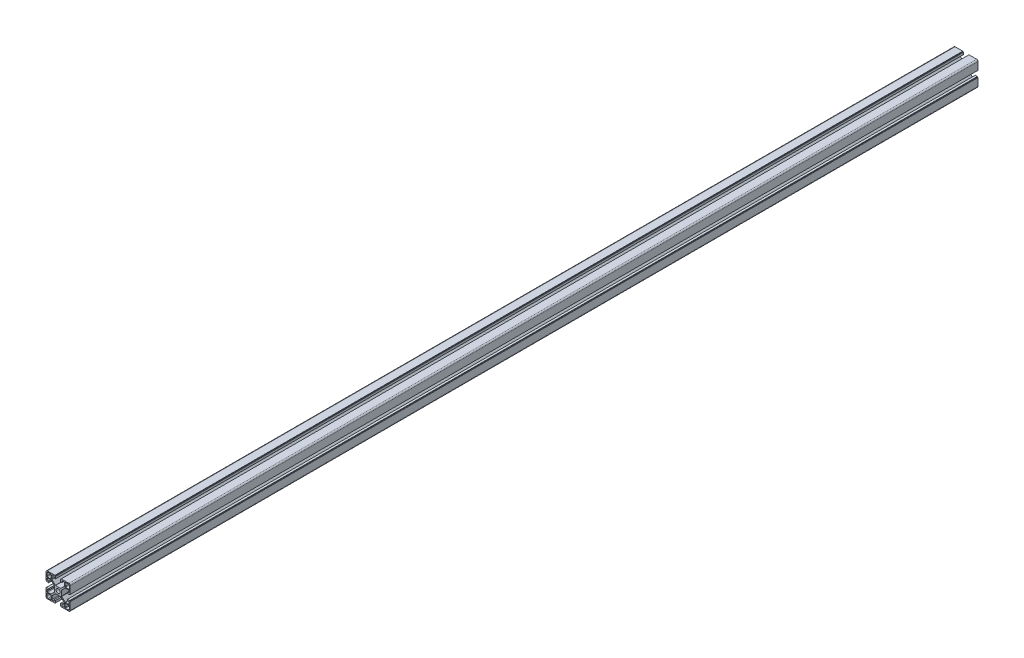
SolidWorks part; units mm, degrees
material "6063-T5"
ref_plane "Front Plane" through (0, 0, 0) normal (0, 0, 1) x (1, 0, 0)
ref_plane "Top Plane" through (0, 0, 0) normal (0, 1, 0) x (1, 0, 0)
ref_plane "Right Plane" through (0, 0, 0) normal (1, 0, 0) x (0, 0, -1)
sketch "Sketch1" plane through (0, 0, 0) normal (0, 0, 1) x (1, 0, 0)
  line L4 (20, 17.75) -> (20, 5.15)
  line L5 (0, -17.7813) -> (0, 18.2) construction
  line L6 (0, 0) -> (38.8613, 0) construction
  line L8 (18.6, 16.35) -> (18.6, 12.2)
  line L10 (11.4, 17.8) -> (11.4, 12.2)
  line L11 (-4.1, 5.85) -> (4.1, 5.85)
  line L14 (5.85, 4.1089) -> (5.85, -4.1089)
  line L17 (12.2, 11.4) -> (17.8, 11.4)
  line L24 (4.15, 19) -> (4.15, 15.4)
  line L25 (4.15, 15.4) -> (6.35, 15.4)
  line L26 (6.35, 15.4) -> (6.35, 16.95)
  line L27 (10.3, 17.2) -> (10.3, 12.0545)
  line L28 (10.0659, 11.489) -> (4.6659, 6.0845)
  line L29 (6.0841, 4.6743) -> (11.4708, 10.0655)
  line L30 (12.0367, 10.3) -> (17.2, 10.3)
  line L31 (18.2, 9.3) -> (18.2, 7.6)
  line L32 (16.95, 6.35) -> (15.4, 6.35)
  line L33 (15.4, 6.35) -> (15.4, 4.15)
  line L34 (15.4, 4.15) -> (19, 4.15)
  line L35 (18.6, 18.6) -> (18.6, -18.6) construction
  line L36 (-18.6, 18.6) -> (18.6, 18.6) construction
  line L37 (-20, 20) -> (20, 20) construction
  line L38 (20, 20) -> (20, -20) construction
  line L40 (7.6, 18.2) -> (9.3, 18.2)
  line L42 (4.15, 19) -> (5.15, 19)
  line L43 (5.15, 19) -> (5.15, 20)
  line L56 (-18.6, 18.6) -> (-18.6, -18.6) construction
  line L57 (-20, 20) -> (-20, -20) construction
  line L60 (5.15, 20) -> (17.75, 20)
  line L91 (-18.6, -18.6) -> (18.6, -18.6) construction
  line L92 (-20, -20) -> (20, -20) construction
  line L93 (12.2, 18.6) -> (16.35, 18.6)
  line L94 (17.9399, 17.9421) -> (20, 20) construction
  line L95 (0, 0) -> (11.4, 11.4094) construction
  line L101 (19, 4.15) -> (19, 5.15)
  line L102 (19, 5.15) -> (20, 5.15)
  line L104 (-5.85, 4.1089) -> (-5.85, -4.1089)
  line L105 (-19, 5.15) -> (-20, 5.15)
  line L106 (-19, 4.15) -> (-19, 5.15)
  line L107 (-12.2, 18.6) -> (-16.35, 18.6)
  line L108 (-5.15, 20) -> (-17.75, 20)
  line L109 (-5.15, 19) -> (-5.15, 20)
  line L110 (-4.15, 19) -> (-5.15, 19)
  line L111 (-7.6, 18.2) -> (-9.3, 18.2)
  line L112 (-15.4, 4.15) -> (-19, 4.15)
  line L113 (-15.4, 6.35) -> (-15.4, 4.15)
  line L114 (-16.95, 6.35) -> (-15.4, 6.35)
  line L115 (-18.2, 9.3) -> (-18.2, 7.6)
  line L116 (-12.0367, 10.3) -> (-17.2, 10.3)
  line L117 (-6.0841, 4.6743) -> (-11.4708, 10.0655)
  line L118 (-10.0659, 11.489) -> (-4.6659, 6.0845)
  line L119 (-10.3, 17.2) -> (-10.3, 12.0545)
  line L120 (-6.35, 15.4) -> (-6.35, 16.95)
  line L121 (-4.15, 15.4) -> (-6.35, 15.4)
  line L122 (-4.15, 19) -> (-4.15, 15.4)
  line L123 (-12.2, 11.4) -> (-17.8, 11.4)
  line L124 (-11.4, 17.8) -> (-11.4, 12.2)
  line L125 (-18.6, 16.35) -> (-18.6, 12.2)
  line L126 (-20, 17.75) -> (-20, 5.15)
  line L127 (-20, -17.75) -> (-20, -5.15)
  line L128 (-18.6, -16.35) -> (-18.6, -12.2)
  line L129 (-11.4, -17.8) -> (-11.4, -12.2)
  line L130 (-12.2, -11.4) -> (-17.8, -11.4)
  line L131 (-4.15, -19) -> (-4.15, -15.4)
  line L132 (-4.15, -15.4) -> (-6.35, -15.4)
  line L133 (-6.35, -15.4) -> (-6.35, -16.95)
  line L134 (-10.3, -17.2) -> (-10.3, -12.0545)
  line L135 (-10.0659, -11.489) -> (-4.6659, -6.0845)
  line L136 (-6.0841, -4.6743) -> (-11.4708, -10.0655)
  line L137 (-12.0367, -10.3) -> (-17.2, -10.3)
  line L138 (-18.2, -9.3) -> (-18.2, -7.6)
  line L139 (-16.95, -6.35) -> (-15.4, -6.35)
  line L140 (-15.4, -6.35) -> (-15.4, -4.15)
  line L141 (-15.4, -4.15) -> (-19, -4.15)
  line L142 (-7.6, -18.2) -> (-9.3, -18.2)
  line L143 (-4.15, -19) -> (-5.15, -19)
  line L144 (-5.15, -19) -> (-5.15, -20)
  line L145 (-5.15, -20) -> (-17.75, -20)
  line L146 (-12.2, -18.6) -> (-16.35, -18.6)
  line L147 (-19, -4.15) -> (-19, -5.15)
  line L148 (-19, -5.15) -> (-20, -5.15)
  line L149 (19, -5.15) -> (20, -5.15)
  line L150 (19, -4.15) -> (19, -5.15)
  line L151 (12.2, -18.6) -> (16.35, -18.6)
  line L152 (5.15, -20) -> (17.75, -20)
  line L153 (5.15, -19) -> (5.15, -20)
  line L154 (4.15, -19) -> (5.15, -19)
  line L155 (7.6, -18.2) -> (9.3, -18.2)
  line L156 (15.4, -4.15) -> (19, -4.15)
  line L157 (15.4, -6.35) -> (15.4, -4.15)
  line L158 (16.95, -6.35) -> (15.4, -6.35)
  line L159 (18.2, -9.3) -> (18.2, -7.6)
  line L160 (12.0367, -10.3) -> (17.2, -10.3)
  line L161 (6.0841, -4.6743) -> (11.4708, -10.0655)
  line L162 (10.0659, -11.489) -> (4.6659, -6.0845)
  line L163 (10.3, -17.2) -> (10.3, -12.0545)
  line L164 (6.35, -15.4) -> (6.35, -16.95)
  line L165 (4.15, -15.4) -> (6.35, -15.4)
  line L166 (4.15, -19) -> (4.15, -15.4)
  line L167 (12.2, -11.4) -> (17.8, -11.4)
  line L168 (-4.1, -5.85) -> (4.1, -5.85)
  line L169 (11.4, -17.8) -> (11.4, -12.2)
  line L170 (18.6, -16.35) -> (18.6, -12.2)
  line L171 (20, -17.75) -> (20, -5.15)
  circle A0 centre (0, 0) radius 3.4
  arc A7 (16.35, 18.6) -> (18.6, 16.35) centre (16.35, 16.35) cw
  arc A8 (20, 17.75) -> (17.75, 20) centre (17.75, 17.75) ccw
  arc A9 (6.35, 16.95) -> (7.6, 18.2) centre (7.6, 16.95) cw
  arc A10 (18.2, 7.6) -> (16.95, 6.35) centre (16.95, 7.6) cw
  arc A11 (17.2, 10.3) -> (18.2, 9.3) centre (17.2, 9.3) cw
  arc A12 (9.3, 18.2) -> (10.3, 17.2) centre (9.3, 17.2) cw
  arc A13 (4.6659, 6.0845) -> (4.1, 5.85) centre (4.1, 6.65) cw
  arc A14 (6.0841, 4.6743) -> (5.85, 4.1089) centre (6.65, 4.1089) ccw
  arc A15 (17.8, 11.4) -> (18.6, 12.2) centre (17.8, 12.2) ccw
  arc A16 (12.2, 18.6) -> (11.4, 17.8) centre (12.2, 17.8) ccw
  arc A17 (11.4, 12.2) -> (12.2, 11.4) centre (12.2, 12.2) ccw
  arc A18 (11.4708, 10.0655) -> (12.0367, 10.3) centre (12.0367, 9.5) cw
  arc A19 (10.3, 12.0545) -> (10.0659, 11.489) centre (9.5, 12.0545) cw
  arc A20 (-10.3, 12.0545) -> (-10.0659, 11.489) centre (-9.5, 12.0545) ccw
  arc A21 (-11.4708, 10.0655) -> (-12.0367, 10.3) centre (-12.0367, 9.5) ccw
  arc A22 (-11.4, 12.2) -> (-12.2, 11.4) centre (-12.2, 12.2) cw
  arc A23 (-12.2, 18.6) -> (-11.4, 17.8) centre (-12.2, 17.8) cw
  arc A24 (-17.8, 11.4) -> (-18.6, 12.2) centre (-17.8, 12.2) cw
  arc A25 (-6.0841, 4.6743) -> (-5.85, 4.1089) centre (-6.65, 4.1089) cw
  arc A26 (-4.6659, 6.0845) -> (-4.1, 5.85) centre (-4.1, 6.65) ccw
  arc A27 (-9.3, 18.2) -> (-10.3, 17.2) centre (-9.3, 17.2) ccw
  arc A28 (-17.2, 10.3) -> (-18.2, 9.3) centre (-17.2, 9.3) ccw
  arc A29 (-18.2, 7.6) -> (-16.95, 6.35) centre (-16.95, 7.6) ccw
  arc A30 (-6.35, 16.95) -> (-7.6, 18.2) centre (-7.6, 16.95) ccw
  arc A31 (-20, 17.75) -> (-17.75, 20) centre (-17.75, 17.75) cw
  arc A32 (-16.35, 18.6) -> (-18.6, 16.35) centre (-16.35, 16.35) ccw
  arc A33 (-16.35, -18.6) -> (-18.6, -16.35) centre (-16.35, -16.35) cw
  arc A34 (-20, -17.75) -> (-17.75, -20) centre (-17.75, -17.75) ccw
  arc A35 (-6.35, -16.95) -> (-7.6, -18.2) centre (-7.6, -16.95) cw
  arc A36 (-18.2, -7.6) -> (-16.95, -6.35) centre (-16.95, -7.6) cw
  arc A37 (-17.2, -10.3) -> (-18.2, -9.3) centre (-17.2, -9.3) cw
  arc A38 (-9.3, -18.2) -> (-10.3, -17.2) centre (-9.3, -17.2) cw
  arc A39 (-4.6659, -6.0845) -> (-4.1, -5.85) centre (-4.1, -6.65) cw
  arc A40 (-6.0841, -4.6743) -> (-5.85, -4.1089) centre (-6.65, -4.1089) ccw
  arc A41 (-17.8, -11.4) -> (-18.6, -12.2) centre (-17.8, -12.2) ccw
  arc A42 (-12.2, -18.6) -> (-11.4, -17.8) centre (-12.2, -17.8) ccw
  arc A43 (-11.4, -12.2) -> (-12.2, -11.4) centre (-12.2, -12.2) ccw
  arc A44 (-11.4708, -10.0655) -> (-12.0367, -10.3) centre (-12.0367, -9.5) cw
  arc A45 (-10.3, -12.0545) -> (-10.0659, -11.489) centre (-9.5, -12.0545) cw
  arc A46 (10.3, -12.0545) -> (10.0659, -11.489) centre (9.5, -12.0545) ccw
  arc A47 (11.4708, -10.0655) -> (12.0367, -10.3) centre (12.0367, -9.5) ccw
  arc A48 (11.4, -12.2) -> (12.2, -11.4) centre (12.2, -12.2) cw
  arc A49 (12.2, -18.6) -> (11.4, -17.8) centre (12.2, -17.8) cw
  arc A50 (17.8, -11.4) -> (18.6, -12.2) centre (17.8, -12.2) cw
  arc A51 (6.0841, -4.6743) -> (5.85, -4.1089) centre (6.65, -4.1089) cw
  arc A52 (4.6659, -6.0845) -> (4.1, -5.85) centre (4.1, -6.65) ccw
  arc A53 (9.3, -18.2) -> (10.3, -17.2) centre (9.3, -17.2) ccw
  arc A54 (17.2, -10.3) -> (18.2, -9.3) centre (17.2, -9.3) ccw
  arc A55 (18.2, -7.6) -> (16.95, -6.35) centre (16.95, -7.6) ccw
  arc A56 (6.35, -16.95) -> (7.6, -18.2) centre (7.6, -16.95) ccw
  arc A57 (20, -17.75) -> (17.75, -20) centre (17.75, -17.75) cw
  arc A58 (16.35, -18.6) -> (18.6, -16.35) centre (16.35, -16.35) ccw
  point P0 (0, 0)
  point P16 (-5.85, 0)
  point P66 (0, 5.85)
  point P120 (5.85, 0)
  point P218 (0, -5.85)
  dimension "D5" = 6.8
  dimension "D6" = 1.4
  dimension "D15" = 5.85
  dimension "D44" = 2.25
  dimension "D25" = 1.25
  dimension "D26" = 1
  dimension "D27" = 0.8
  dimension "D7" = 1.1
  dimension "D8" = 1.1
  dimension "D9" = 1.8
  dimension "D10" = 2.2
  dimension "D11" = 4.6
  dimension "D12" = 1.8
  dimension "D13" = 2.2
  dimension "D14" = 5.85
  dimension "D16" = 1.4
  dimension "D17" = 4.15
  dimension "D18" = 1
  dimension "D19" = 1
  dimension "D20" = 10.3
  dimension "D21" = 4.15
  dimension "D22" = 2
  dimension "D23" = 45.024
  dimension "D24" = 1
  dimension "D41" = 10.3
  dimension "D60" = 14.15
  dimension "D73" = 1
  dimension "D74" = 1
  dimension "D82" = 14.15
  dimension "D3" = 4.6
extrude "Boss-Extrude1" add sketch "Sketch1" along normal blind 1500
sketch "Sketch2" plane through (0, 20, 0) normal (0, 1, 0) x (1, 0, 0)
  line L0 (-20, -1500) -> (-20, 0) construction
  line L1 (-20, -600) -> (20, -600)
  line L2 (-20, -600) -> (-20, -1500)
  line L3 (-20, -1500) -> (20, -1500)
  line L4 (20, -600) -> (20, -1500)
  line L5 (-5.15, 0) -> (-17.75, 0) construction
  dimension "D1" = 600
